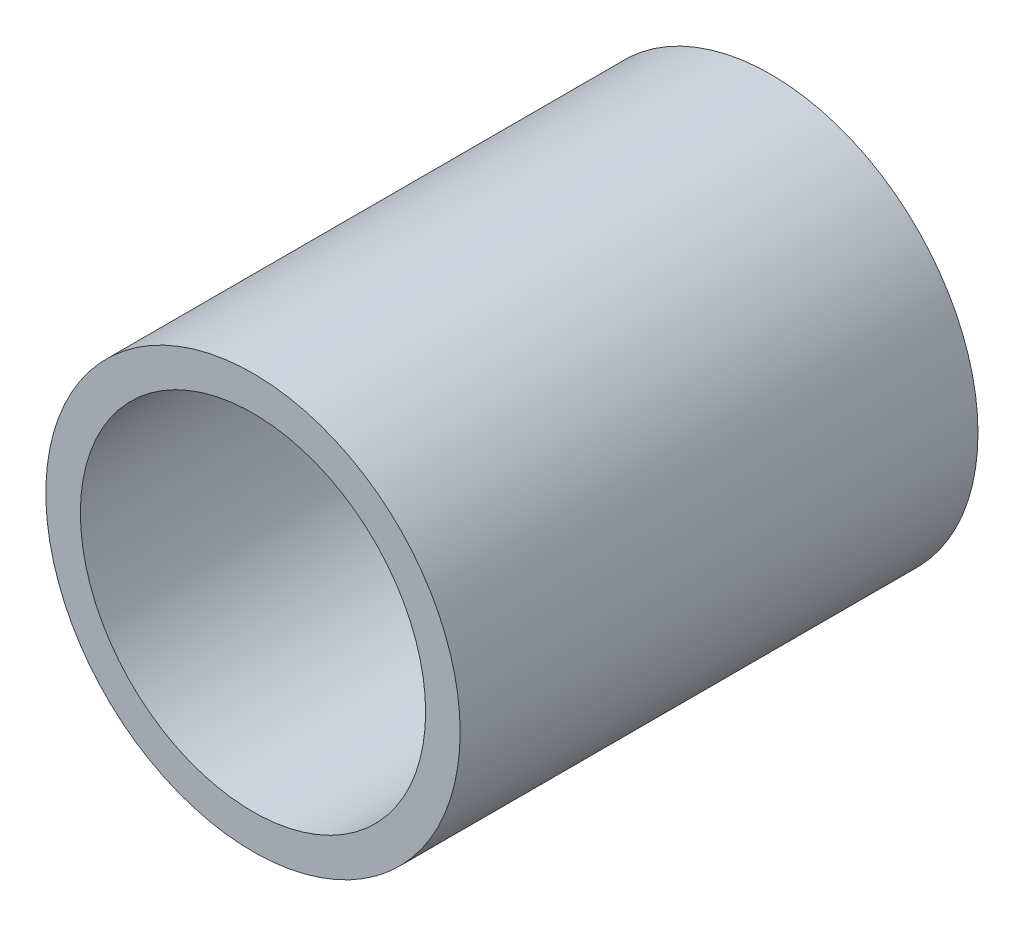
SolidWorks part; units mm, degrees
material "Acrílico (médio-alto impacto)"
ref_plane "Plano frontal" through (0, 0, 0) normal (0, 0, 1) x (1, 0, 0)
ref_plane "Plano superior" through (0, 0, 0) normal (0, 1, 0) x (1, 0, 0)
ref_plane "Plano direito" through (0, 0, 0) normal (1, 0, 0) x (0, 0, -1)
sketch "Esboço1" plane through (0, 0, 0) normal (0, 0, 1) x (1, 0, 0)
  circle A0 centre (0, 0) radius 6
  circle A1 centre (0, 0) radius 5
  dimension "D1" = 12
  dimension "D2" = 10
extrude "Ressalto-extrusão1" add sketch "Esboço1" along normal blind 15
